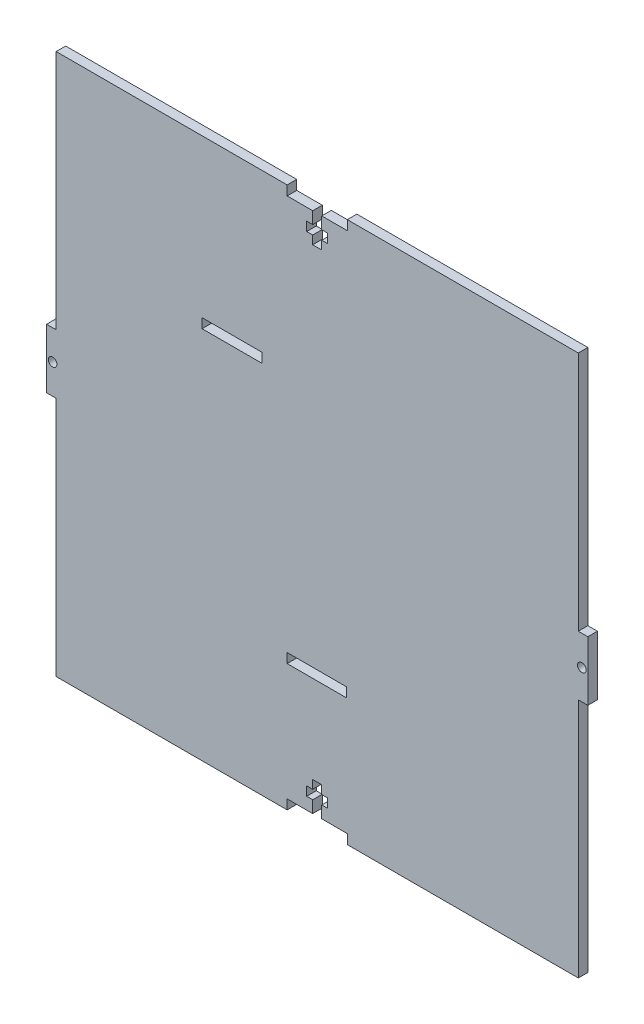
SolidWorks part; units mm, degrees
ref_plane "Front Plane" through (0, 0, 0) normal (0, 0, 1) x (1, 0, 0)
ref_plane "Top Plane" through (0, 0, 0) normal (0, 1, 0) x (1, 0, 0)
ref_plane "Right Plane" through (0, 0, 0) normal (1, 0, 0) x (0, 0, -1)
sketch "Sketch3" plane through (0, 0, 0) normal (0, 0, 1) x (1, 0, 0)
  line L0 (-90, 0) -> (90, 0) construction
  line L1 (-90, 90) -> (90, 90)
  line L2 (-90, 90) -> (-90, -90)
  line L3 (-90, -90) -> (90, -90)
  line L4 (90, 90) -> (90, -90)
  line L5 (-90, 0) -> (42.6717, 0) construction
  line L6 (0, 90) -> (0, -90) construction
  line L7 (-38.2869, 37.6148) -> (-38.2869, 34.4348)
  line L8 (-38.2869, 34.4348) -> (-18.2869, 34.4348)
  line L9 (-18.2869, 34.4348) -> (-18.2869, 37.6148)
  line L10 (-18.2869, 37.6148) -> (-38.2869, 37.6148)
  line L11 (9.75, -44.6797) -> (9.75, -47.8597)
  line L12 (9.75, -47.8597) -> (-10, -47.8597)
  line L13 (-10, -47.8597) -> (-10, -44.6797)
  line L14 (-10, -44.6797) -> (9.75, -44.6797)
  dimension "D1" = 180
  dimension "D3" = 180
extrude "Boss-Extrude1" add sketch "Sketch3" along normal blind 3.18
sketch "Sketch4" plane through (0, 0, 3.18) normal (0, 0, 1) x (1, 0, 0)
  line L0 (-90, 90) -> (-90, -90) construction
  line L1 (90, -90) -> (90, 90) construction
  line L2 (-90, 0) -> (90, 0) construction
  line L3 (0.9399, -90) -> (0, -90) construction
  line L4 (90, 90) -> (-90, 90) construction
  line L5 (0, -90) -> (0, 90) construction
  line L6 (1.5, 86.82) -> (10, 86.82)
  line L7 (-10, 90) -> (10, 90)
  line L8 (-10, 90) -> (-10, 86.82)
  line L9 (-10, 86.82) -> (-1.5, 86.82)
  line L10 (10, 90) -> (10, 86.82)
  line L11 (-3.5, 82.82) -> (-1.5, 82.82)
  line L12 (-3.5, 82.82) -> (-3.5, 79.82)
  line L13 (-3.5, 79.82) -> (-1.5, 79.82)
  line L14 (3.5, 82.82) -> (3.5, 79.82)
  line L15 (1.5, 82.82) -> (3.5, 82.82)
  line L16 (-1.5, 86.82) -> (-1.5, 82.82)
  line L17 (-1.5, 77) -> (1.5, 77)
  line L18 (1.5, 86.82) -> (1.5, 82.82)
  line L19 (-90, -90) -> (90, -90) construction
  line L20 (1.5, 79.82) -> (3.5, 79.82)
  line L21 (-1.5, 79.82) -> (-1.5, 77)
  line L22 (1.5, 79.82) -> (1.5, 77)
  line L23 (1.5, -79.82) -> (1.5, -77)
  line L24 (-1.5, -79.82) -> (-1.5, -77)
  line L25 (1.5, -79.82) -> (3.5, -79.82)
  line L26 (1.5, -86.82) -> (1.5, -82.82)
  line L27 (-1.5, -77) -> (1.5, -77)
  line L28 (-1.5, -86.82) -> (-1.5, -82.82)
  line L29 (1.5, -82.82) -> (3.5, -82.82)
  line L30 (3.5, -82.82) -> (3.5, -79.82)
  line L31 (-3.5, -79.82) -> (-1.5, -79.82)
  line L32 (-3.5, -82.82) -> (-3.5, -79.82)
  line L33 (-3.5, -82.82) -> (-1.5, -82.82)
  line L34 (10, -90) -> (10, -86.82)
  line L35 (-10, -86.82) -> (-1.5, -86.82)
  line L36 (-10, -90) -> (-10, -86.82)
  line L37 (-10, -90) -> (10, -90)
  line L38 (1.5, -86.82) -> (10, -86.82)
  dimension "D1" = 20
  dimension "D2" = 3.18
  dimension "D3" = 4
  dimension "D4" = 3
  dimension "D5" = 3
  dimension "D6" = 13
  dimension "D7" = 7
sketch "Sketch5" plane through (0, 0, 3.18) normal (0, 0, 1) x (1, 0, 0)
  line L0 (-90, 0) -> (90, 0) construction
  line L1 (-90, 90) -> (-86.82, 90)
  line L2 (-90, 90) -> (-90, 9.875)
  line L3 (-90, 9.875) -> (-86.82, 9.875)
  line L4 (-86.82, 90) -> (-86.82, 9.875)
  line L5 (-90, -90) -> (-86.82, -90)
  line L6 (-90, -90) -> (-90, -9.875)
  line L7 (-90, -9.875) -> (-86.82, -9.875)
  line L8 (-86.82, -90) -> (-86.82, -9.875)
  line L9 (-90, 90) -> (-90, -90) construction
  line L10 (0, 90) -> (0, -90) construction
  line L11 (86.82, -90) -> (86.82, -9.875)
  line L12 (90, -9.875) -> (86.82, -9.875)
  line L13 (90, -90) -> (90, -9.875)
  line L14 (90, -90) -> (86.82, -90)
  line L15 (86.82, 90) -> (86.82, 9.875)
  line L16 (90, 9.875) -> (86.82, 9.875)
  line L17 (90, 90) -> (90, 9.875)
  line L18 (90, 90) -> (86.82, 90)
  circle A0 centre (-88, 0) radius 1.436
  circle A1 centre (88, 0) radius 1.436
  dimension "D4" = 2.872
  dimension "D5" = 2
  dimension "D1" = 3.18
  dimension "D2" = 3.18
  dimension "D3" = 19.75
extrude "Cut-Extrude1" cut sketch "Sketch4" against normal through all
extrude "Cut-Extrude2" cut sketch "Sketch5" against normal through all
